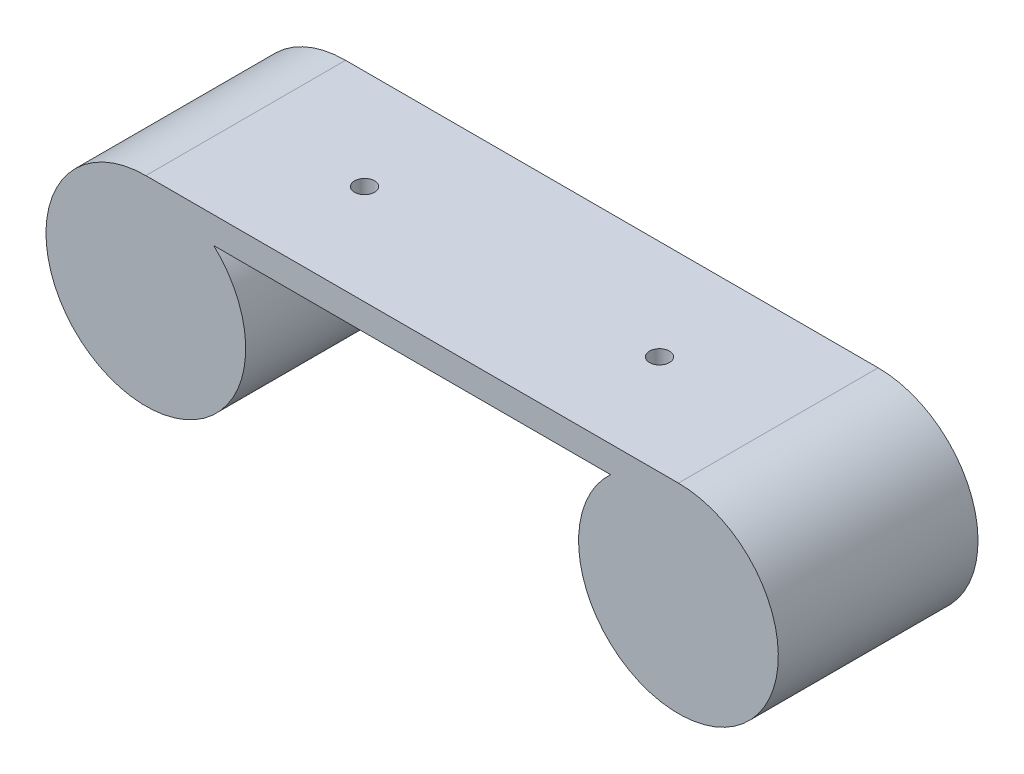
SolidWorks part; units mm, degrees
ref_plane "Front Plane" through (0, 0, 0) normal (0, 0, 1) x (1, 0, 0)
ref_plane "Top Plane" through (0, 0, 0) normal (0, 1, 0) x (1, 0, 0)
ref_plane "Right Plane" through (0, 0, 0) normal (1, 0, 0) x (0, 0, -1)
sketch "Sketch1" plane through (0, 0, 0) normal (0, 0, 1) x (1, 0, 0)
  line L0 (-40, 0) -> (40, 0)
  line L6 (-40, 15) -> (40, 15)
  line L9 (-29.8023, 11.0003) -> (29.8023, 11.0003)
  circle A1 centre (-40, 0) radius 9.45
  circle A3 centre (40, 0) radius 9.45
  arc A6 (-40, 15) -> (-29.8023, 11.0003) centre (-40, 0) ccw
  arc A7 (29.8023, 11.0003) -> (40, 15) centre (40, 0) ccw
  point P4 (0, 0)
  dimension "D1" = 18.9
  dimension "D2" = 30
  dimension "D3" = 30
  dimension "D4" = 18.9
  dimension "D5" = 80
extrude "Boss-Extrude1" add sketch "Sketch1" along normal blind 30
sketch "Sketch2" plane through (0, 0, 30) normal (0, 0, 1) x (1, 0, 0)
  line L2 (0, 11) -> (9.563, 11)
  line L4 (-29.8023, 11.0003) -> (29.8023, 11.0003) construction
  line L5 (-11.8022, 11.0003) -> (11.8022, 11.0003)
  arc A0 (-8.0467, 7.5) -> (8.0467, 7.5) centre (0, 0) ccw
  circle A1 centre (0, 0) radius 4
  circle A2 centre (7.5, 0) radius 1.75
  circle A3 centre (0, -7.5) radius 1.75
  circle A4 centre (-7.5, 0) radius 1.75
  circle A5 centre (0, 7.5) radius 1.75
  arc A6 (-8.0467, 7.5) -> (-11.8022, 11.0003) centre (-12.85, 6.1114) ccw
  arc A7 (8.0467, 7.5) -> (11.8022, 11.0003) centre (12.85, 6.1114) cw
  point P5 (0, 0)
  dimension "D1" = 22
  dimension "D2" = 8
  dimension "D3" = 3.5
  dimension "D4" = 3.5
  dimension "D5" = 3.5
  dimension "D6" = 3.5
  dimension "D7" = 5
  dimension "D8" = 5
sketch "Sketch3" plane through (0, 15, 0) normal (0, 1, 0) x (1, 0, 0)
  line L0 (0, 0) -> (0, -30) construction
  line L1 (0, -15) -> (22.15, -15) construction
  line L2 (0, -15) -> (-22.15, -15) construction
  line L3 (-40, -30) -> (40, -30) construction
  circle A0 centre (-22.15, -15) radius 1.5
  circle A1 centre (22.15, -15) radius 1.5
  point P7 (0, -15.3372)
  dimension "D3" = 3
  dimension "D1" = 22.15
  dimension "D2" = 22.15
extrude "Cut-Extrude1" cut sketch "Sketch3" against normal blind 6
sketch "Sketch5" plane through (0, 0, 30) normal (0, 0, 1) x (1, 0, 0)
  circle A0 centre (-40, 0) radius 9.45
  circle A1 centre (40, 0) radius 9.45
extrude "Boss-Extrude2" add sketch "Sketch5" against normal blind 2
